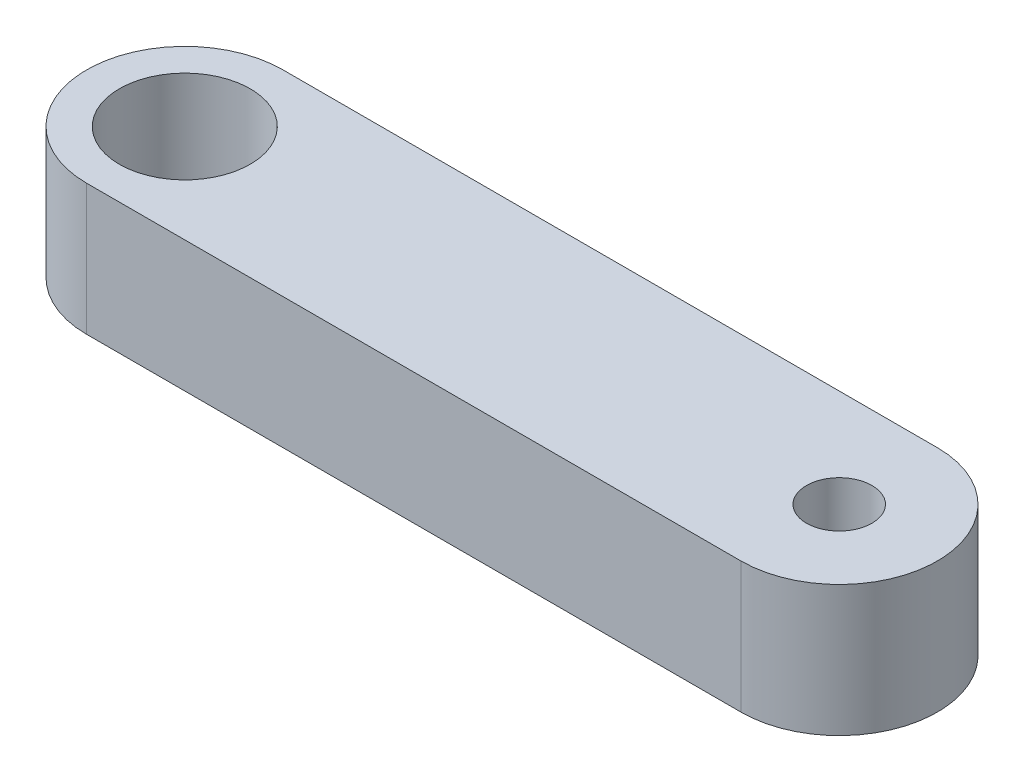
SolidWorks part; units mm, degrees
ref_plane "Front Plane" through (0, 0, 0) normal (0, 0, 1) x (1, 0, 0)
ref_plane "Top Plane" through (0, 0, 0) normal (0, 1, 0) x (1, 0, 0)
ref_plane "Right Plane" through (0, 0, 0) normal (1, 0, 0) x (0, 0, -1)
sketch "Sketch1" plane through (0, 0, 0) normal (0, 1, 0) x (1, 0, 0)
  line L0 (0, 0) -> (50, 0)
  line L1 (50, 0) -> (50, 15) construction
  line L2 (0, 0) -> (0, 15) construction
  line L3 (0, 15) -> (50, 15)
  arc A0 (0, 15) -> (0, 0) centre (0, 7.5) ccw
  arc A1 (50, 0) -> (50, 15) centre (50, 7.5) ccw
  circle A2 centre (50, 7.5) radius 2.5
  circle A3 centre (0, 7.5) radius 5
  dimension "D3" = 10
  dimension "D4" = 5
  dimension "D1" = 50
  dimension "D2" = 15
extrude "Boss-Extrude1" add sketch "Sketch1" along normal blind 10
